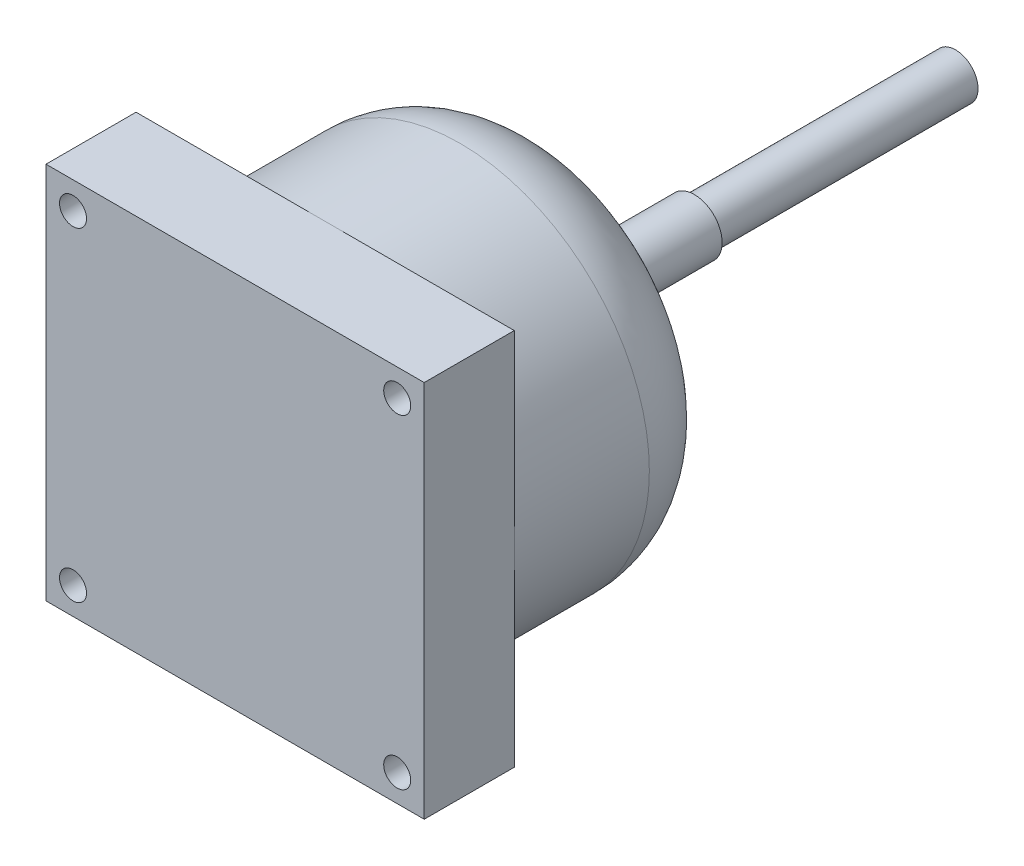
SolidWorks part; units mm, degrees
ref_plane "Plano frontal" through (0, 0, 0) normal (0, 0, 1) x (1, 0, 0)
ref_plane "Plano superior" through (0, 0, 0) normal (0, 1, 0) x (1, 0, 0)
ref_plane "Plano direito" through (0, 0, 0) normal (1, 0, 0) x (0, 0, -1)
sketch "Esboço1" plane through (0, 0, 0) normal (0, 0, 1) x (1, 0, 0)
  circle A0 centre (-33.2954, 25.4525) radius 21
extrude "Ressalto-extrusão1" add sketch "Esboço1" along normal blind 46
fillet "Filete1" radius 10 2 edges at (-12.2954, 25.4525, 46) (-12.2954, 25.4525, 0)
sketch "Esboço2" plane through (0, 0, 0) normal (0, 0, -1) x (-1, 0, 0)
  circle A0 centre (33.2954, 25.4525) radius 3.0794
extrude "Ressalto-extrusão2" add sketch "Esboço2" along normal blind 16
sketch "Esboço3" plane through (0, 0, -16) normal (0, 0, -1) x (-1, 0, 0)
  circle A0 centre (33.2954, 25.4525) radius 2.5
extrude "Ressalto-extrusão3" add sketch "Esboço3" along normal blind 29
ref_plane "Plano1" through (0, 0, 25) normal (0, 0, 1) x (1, 0, 0)
sketch "Esboço4" plane through (0, 0, 25) normal (0, 0, 1) x (1, 0, 0)
  line L0 (-33.2954, 46.4525) -> (-12.2954, 46.4525)
  line L1 (-12.2954, 46.4525) -> (-12.2954, 4.4525)
  line L2 (-12.2954, 4.4525) -> (-54.2954, 4.4525)
  line L3 (-54.2954, 4.4525) -> (-54.2954, 46.4525)
  line L4 (-54.2954, 46.4525) -> (-33.2954, 46.4525)
  circle A0 centre (-33.2954, 25.4525) radius 21 construction
extrude "Ressalto-extrusão4" add sketch "Esboço4" along normal blind 10
sketch "Esboço5" plane through (0, 0, 25) normal (0, 0, 1) x (1, 0, 0)
  circle A0 centre (-33.2954, 25.4525) radius 21
extrude "Corte-extrusão2" cut sketch "Esboço5" along normal through all
sketch "Esboço6" plane through (0, 0, 25) normal (0, 0, 1) x (1, 0, 0)
  circle A0 centre (-33.2954, 25.4525) radius 21
extrude "Ressalto-extrusão5" add sketch "Esboço6" along normal blind 10
sketch "Esboço7" plane through (0, 0, 25) normal (0, 0, -1) x (-1, 0, 0)
  line L0 (12.2954, 25.4525) -> (12.2954, 46.4525) construction
  line L1 (12.2954, 46.4525) -> (33.2954, 46.4525) construction
  line L2 (54.2954, 46.4525) -> (54.2954, 25.4525) construction
  line L3 (33.2954, 46.4525) -> (54.2954, 46.4525) construction
  line L4 (54.2954, 25.4525) -> (54.2954, 4.4525) construction
  line L5 (54.2954, 4.4525) -> (33.2954, 4.4525) construction
  line L6 (12.2954, 4.4525) -> (12.2954, 25.4525) construction
  line L7 (33.2954, 4.4525) -> (12.2954, 4.4525) construction
  circle A0 centre (15.2954, 43.4525) radius 1.5
  circle A1 centre (51.2954, 43.4525) radius 1.5
  circle A2 centre (51.2954, 7.4525) radius 1.5
  circle A3 centre (15.2954, 7.4525) radius 1.5
  dimension "D3" = 3
  dimension "D4" = 3
  dimension "D9" = 3
  dimension "D10" = 3
  dimension "D11" = 3
  dimension "D1" = 3
  dimension "D2" = 3
  dimension "D5" = 3
  dimension "D6" = 3
  dimension "D7" = 3
  dimension "D8" = 3
  dimension "D12" = 3
extrude "Corte-extrusão3" cut sketch "Esboço7" against normal through all
